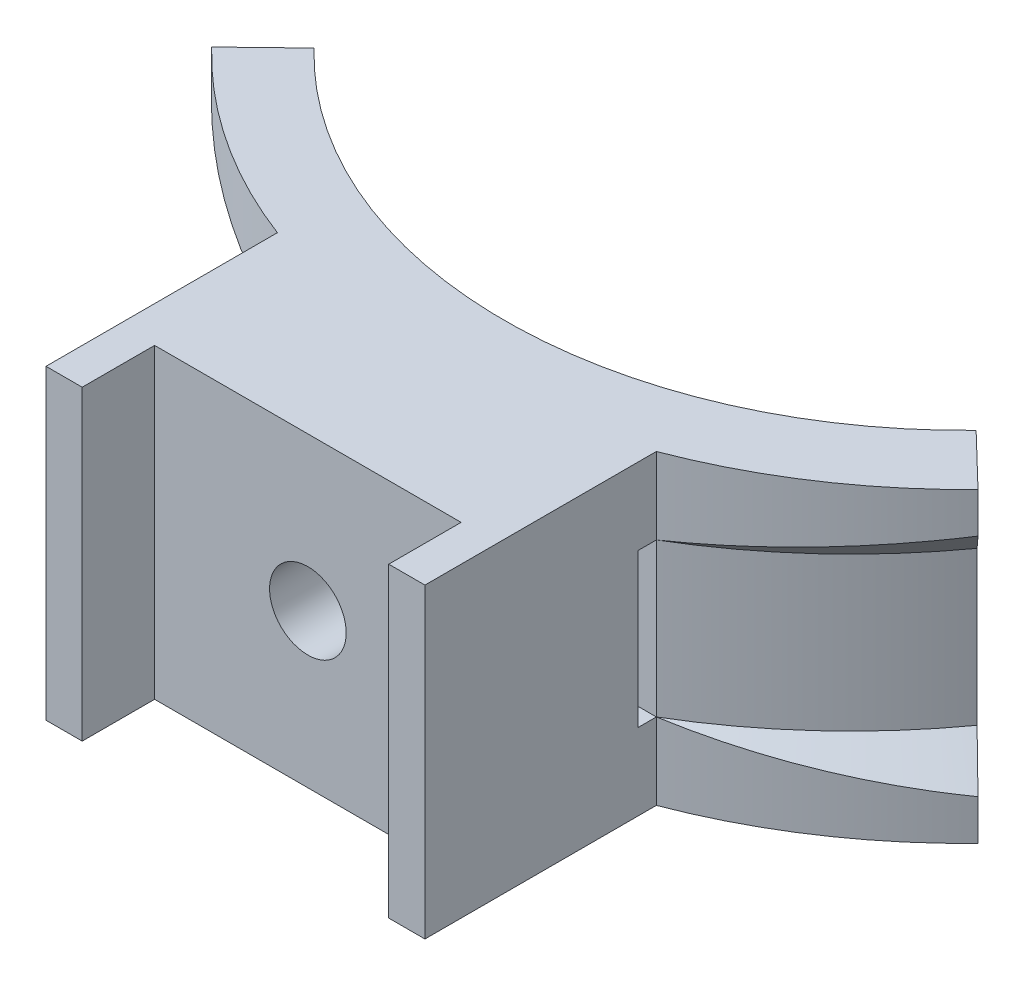
SolidWorks part; units mm, degrees
ref_plane "Front Plane" through (0, 0, 0) normal (0, 0, 1) x (1, 0, 0)
ref_plane "Top Plane" through (0, 0, 0) normal (0, 1, 0) x (1, 0, 0)
ref_plane "Right Plane" through (0, 0, 0) normal (1, 0, 0) x (0, 0, -1)
sketch "Sketch1" plane through (0, 0, 0) normal (0, 1, 0) x (1, 0, 0)
  line L0 (-12.7, -54.385) -> (12.7, -54.385)
  line L1 (-27.4303, -26.4422) -> (-31.75, -30.6063)
  line L2 (27.4303, -26.4422) -> (31.75, -30.6063)
  line L3 (15.7, -41.2107) -> (15.7, -60.385)
  line L5 (-15.7, -41.2107) -> (-15.7, -60.385)
  line L6 (-15.7, -60.385) -> (-12.7, -60.385)
  line L7 (-12.7, -54.385) -> (-12.7, -60.385)
  line L10 (15.7, -60.385) -> (12.7, -60.385)
  line L11 (12.7, -54.385) -> (12.7, -60.385)
  arc A0 (-27.4303, -26.4422) -> (27.4303, -26.4422) centre (0, 0) ccw
  arc A1 (15.7, -41.2107) -> (31.75, -30.6063) centre (0, 0) ccw
  arc A2 (-31.75, -30.6063) -> (-15.7, -41.2107) centre (0, 0) ccw
  point P5 (0, -54.385)
  dimension "D1" = 76.2
  dimension "D2" = 6
  dimension "D3" = 54.385
  dimension "D5" = 3
  dimension "D6" = 6
  dimension "D7" = 25.4
  dimension "D8" = 63.5
extrude "Boss-Extrude1" add sketch "Sketch1" along normal blind 25.4
sketch "Sketch2" plane through (15.7, 0, 0) normal (1, 0, 0) x (0, 0, -1)
  line L0 (-41.2107, 25.4) -> (-41.2107, 0) construction
  line L1 (-41.2107, 19.05) -> (-42.7107, 19.05)
  line L2 (-41.2107, 19.05) -> (-41.2107, 6.35)
  line L3 (-41.2107, 6.35) -> (-42.7107, 6.35)
  line L4 (-42.7107, 19.05) -> (-42.7107, 6.35)
  point P6 (-41.2107, 12.7)
  point P7 (-41.2107, 12.7)
  dimension "D1" = 1.5
  dimension "D2" = 12.7
extrude "Cut-Extrude1" cut sketch "Sketch2" against normal through all
sketch "Sketch3" plane through (0, 6.35, 0) normal (0, 1, 0) x (1, 0, 0)
  line L0 (31.75, -30.6063) -> (27.4303, -26.4422) construction
  line L1 (31.75, -30.6063) -> (29.5901, -28.5243)
  arc A0 (29.5901, -28.5243) -> (15.7, -41.2107) centre (-7.7063, -1.6363) cw
  circle A1 centre (0, 0) radius 38.1 construction
  arc A2 (-27.4303, -26.4422) -> (27.4303, -26.4422) centre (0, 0) ccw construction
  arc A3 (15.7, -41.2107) -> (31.75, -30.6063) centre (0, 0) ccw construction
  arc A4 (15.7, -41.2107) -> (31.75, -30.6063) centre (0, 0) ccw
  dimension "D1" = 3
extrude "Cut-Extrude2" cut sketch "Sketch3" along normal up to surface (12.7 mm away) up to face at (0, 19.05, 41.9607)
ref_plane "Plane1" through (0, 0, 0) normal (1, 0, 0) x (0, 0, -1)
mirror "Mirror1" about plane through (0, 0, 0) normal (1, 0, 0) of "Cut-Extrude2"
sketch "Sketch6" plane through (0, 0, 54.385) normal (0, 0, 1) x (1, 0, 0)
  line L0 (-12.7, 25.4) -> (12.7, 0) construction
  circle A0 centre (0, 12.7) radius 3.175
  dimension "D1" = 6.35
extrude "Cut-Extrude4" cut sketch "Sketch6" against normal through all
ref_plane "Plane2" through (0, 0, 38.1) normal (0, 0, 1) x (1, 0, 0)
sketch "Sketch7" plane through (0, 0, 38.1) normal (0, 0, 1) x (1, 0, 0)
  line L1 (6.4158, 12.7) -> (3.2079, 18.2563)
  line L2 (3.2079, 18.2563) -> (-3.2079, 18.2563)
  line L3 (-3.2079, 18.2563) -> (-6.4158, 12.7)
  line L4 (-6.4158, 12.7) -> (-3.2079, 7.1438)
  line L5 (-3.2079, 7.1438) -> (3.2079, 7.1438)
  line L6 (3.2079, 7.1438) -> (6.4158, 12.7)
  circle A0 centre (0, 12.7) radius 5.5563 construction
  dimension "D1" = 11.1125
extrude "Cut-Extrude5" cut sketch "Sketch7" along normal blind 4.3656 and the other way through all
sketch "Sketch8" plane through (0, 0, 0) normal (0.694, 0, -0.72) x (-0.72, 0, -0.694)
  line L0 (-44.1, 19.05) -> (-41.1, 19.05)
  line L1 (-44.1, 19.05) -> (-41.1, 19.05) construction
  line L2 (-41.1, 19.05) -> (-44.1, 22.05)
  line L3 (-44.1, 25.4) -> (-44.1, 19.05) construction
  line L4 (-44.1, 22.05) -> (-44.1, 19.05)
  line L6 (-41.1, 19.05) -> (-41.1, 6.35) construction
  dimension "D1" = 45
sketch "Sketch9" plane through (0, 19.05, 0) normal (0, -1, 0) x (1, 0, 0)
  arc A0 (29.5901, 28.5243) -> (15.7, 41.2107) centre (-7.7063, 1.6363) ccw construction
  arc A1 (29.5901, 28.5243) -> (15.7, 41.2107) centre (-7.7063, 1.6363) ccw
sweep "Cut-Sweep1" cut profiles "Sketch8" path "Sketch9"
ref_plane "Plane3" through (0, 12.7, 0) normal (0, 1, 0) x (1, 0, 0)
mirror "Mirror2" about plane through (0, 12.7, 0) normal (0, 1, 0) of "Cut-Sweep1"
mirror "Mirror3" about plane through (0, 0, 0) normal (1, 0, 0) of "Mirror2", "Cut-Sweep1"
